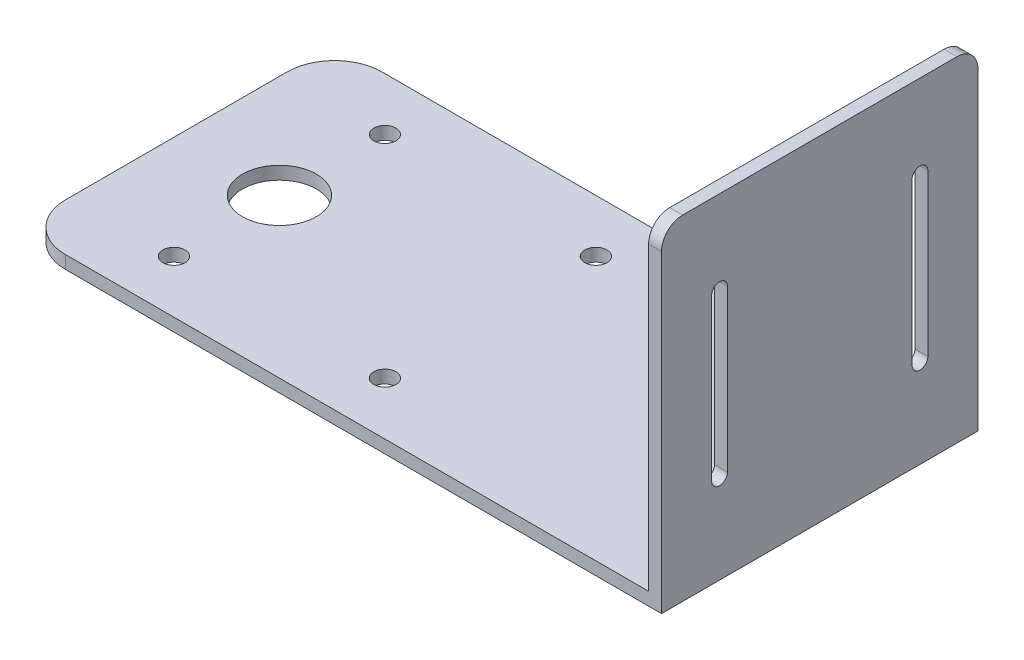
SolidWorks part; units mm, degrees
ref_plane "前视基准面" through (0, 0, 0) normal (0, 0, 1) x (1, 0, 0)
ref_plane "上视基准面" through (0, 0, 0) normal (0, 1, 0) x (1, 0, 0)
ref_plane "右视基准面" through (0, 0, 0) normal (1, 0, 0) x (0, 0, -1)
sketch "草图1" plane through (0, 0, 0) normal (0, 1, 0) x (1, 0, 0)
  line L1 (-61, 30) -> (61, 30)
  line L2 (-61, 30) -> (-61, -30)
  line L3 (-61, -30) -> (61, -30)
  line L4 (61, 30) -> (61, -30)
  circle A0 centre (-41.45, 0) radius 7
  circle A1 centre (-41.45, 20) radius 2.1
  circle A2 centre (-1.45, 20) radius 2.1
  circle A3 centre (-1.45, -20) radius 2.1
  circle A4 centre (-41.45, -20) radius 2.1
  dimension "D5" = 14
  dimension "D7" = 4.2
  dimension "D1" = 122
  dimension "D2" = 60
  dimension "D3" = 30
  dimension "D4" = 61
  dimension "D6" = 102.45
  dimension "D8" = 10
  dimension "D9" = 2
  dimension "D10" = 2
extrude "凸台-拉伸1" add sketch "草图1" along normal blind 2.45
fillet "圆角1" radius 9 2 edges at (-61, 1.225, -30) (-61, 1.225, 30)
sketch "草图2" plane through (0, 2.45, 0) normal (0, 1, 0) x (1, 0, 0)
  line L0 (-52, -30) -> (61, -30) construction
  line L1 (61, 30) -> (58.55, 30)
  line L2 (61, 30) -> (61, -30)
  line L3 (61, -30) -> (58.55, -30)
  line L4 (58.55, 30) -> (58.55, -30)
  dimension "D1" = 2.45
extrude "凸台-拉伸2" add sketch "草图2" along normal blind 61
fillet "圆角2" radius 4 2 edges at (59.775, 63.45, -30) (59.775, 63.45, 30)
sketch "草图3" plane through (58.55, 0, 0) normal (-1, 0, 0) x (0, 0, 1)
  line L0 (0, 63.45) -> (0, 0) construction
  line L1 (-26, 63.45) -> (26, 63.45) construction
  line L2 (-30, 59.45) -> (-30, 2.45) construction
  line L3 (-21, 0) -> (21, 0) construction
  line L4 (-20.5, 47.5) -> (-20.5, 17)
  line L5 (-17.5, 47.5) -> (-17.5, 17)
  line L6 (17.5, 47.5) -> (17.5, 17)
  line L7 (20.5, 47.5) -> (20.5, 17)
  arc A0 (-17.5, 47.5) -> (-20.5, 47.5) centre (-19, 47.5) ccw
  arc A1 (-20.5, 17) -> (-17.5, 17) centre (-19, 17) ccw
  arc A2 (20.5, 17) -> (17.5, 17) centre (19, 17) cw
  arc A3 (17.5, 47.5) -> (20.5, 47.5) centre (19, 47.5) cw
  dimension "D1" = 3
  dimension "D2" = 3
  dimension "D3" = 11
  dimension "D4" = 11
  dimension "D5" = 30.5
  dimension "D6" = 17
extrude "切除-拉伸1" cut sketch "草图3" against normal blind 61
